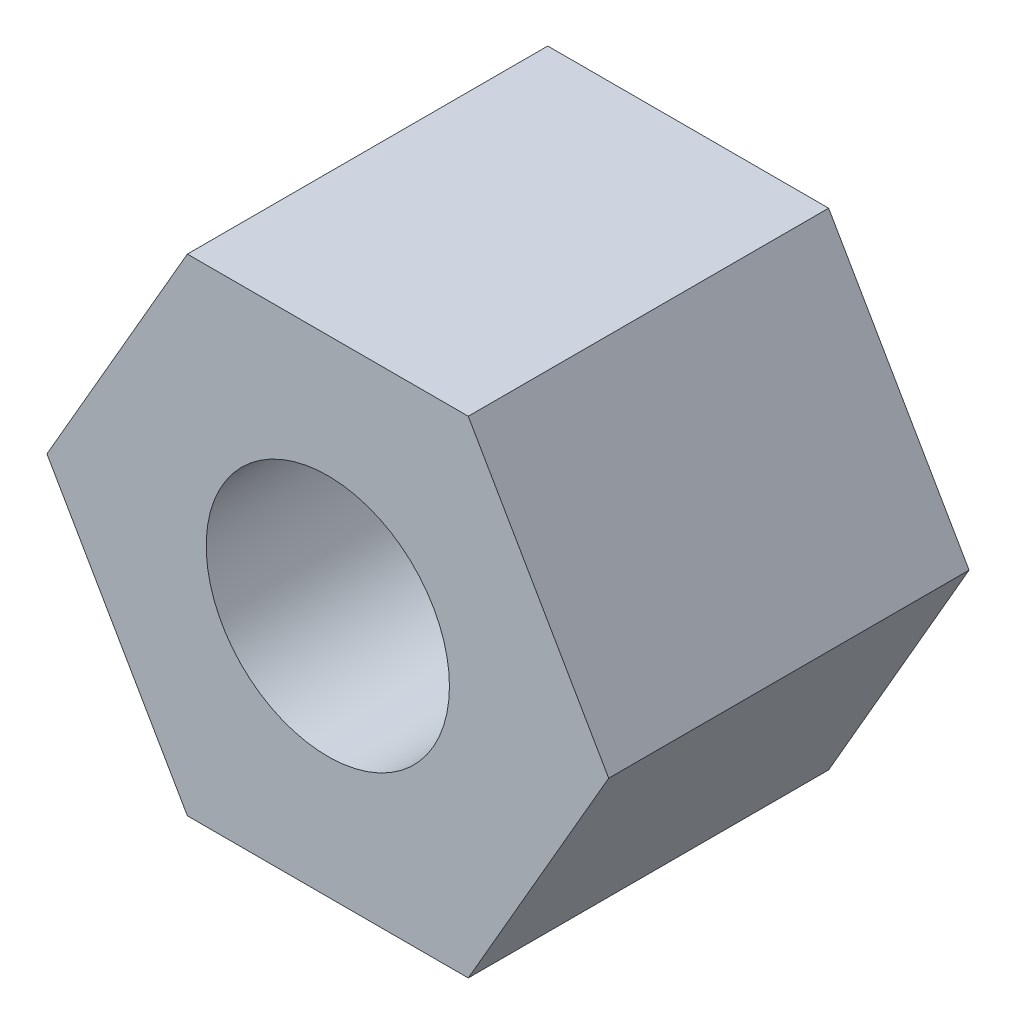
SolidWorks part; units mm, degrees
material "Nylon 6/10"
ref_plane "Front Plane" through (0, 0, 0) normal (0, 0, 1) x (1, 0, 0)
ref_plane "Top Plane" through (0, 0, 0) normal (0, 1, 0) x (1, 0, 0)
ref_plane "Right Plane" through (0, 0, 0) normal (1, 0, 0) x (0, 0, -1)
sketch "Sketch1" plane through (0, 0, 0) normal (0, 0, 1) x (1, 0, 0)
  line L1 (3.1177, 0) -> (1.5588, 2.7)
  line L2 (1.5588, 2.7) -> (-1.5588, 2.7)
  line L3 (-1.5588, 2.7) -> (-3.1177, 0)
  line L4 (-3.1177, 0) -> (-1.5588, -2.7)
  line L5 (-1.5588, -2.7) -> (1.5588, -2.7)
  line L6 (1.5588, -2.7) -> (3.1177, 0)
  circle A0 centre (0, 0) radius 2.7 construction
  circle A1 centre (0, 0) radius 1.35
  dimension "D2" = 2.7
  dimension "D1" = 5.4
extrude "Boss-Extrude1" add sketch "Sketch1" along normal blind 4
